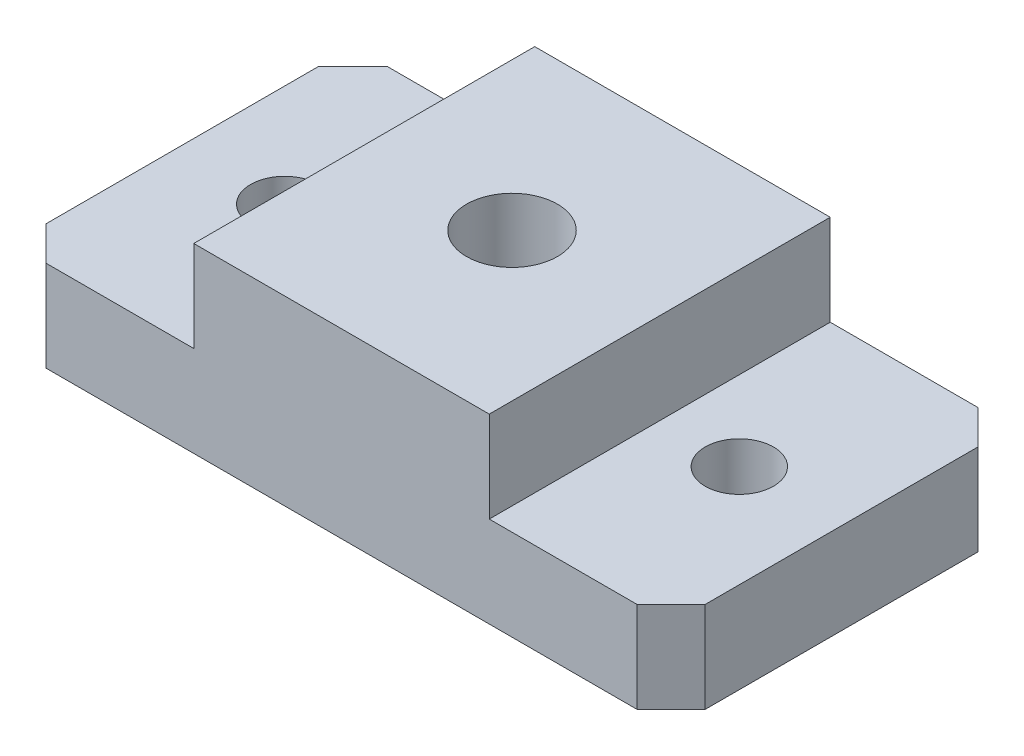
SolidWorks part; units mm, degrees
ref_plane "Front Plane" through (0, 0, 0) normal (0, 0, 1) x (1, 0, 0)
ref_plane "Top Plane" through (0, 0, 0) normal (0, 1, 0) x (1, 0, 0)
ref_plane "Right Plane" through (0, 0, 0) normal (1, 0, 0) x (0, 0, -1)
sketch "Sketch1" plane through (0, 0, 0) normal (0, 1, 0) x (1, 0, 0)
  line L0 (-20, 0) -> (20, 0) construction
  line L1 (-29, 15) -> (29, 15)
  line L2 (-29, 15) -> (-29, -15)
  line L3 (-29, -15) -> (29, -15)
  line L4 (29, 15) -> (29, -15)
  line L5 (-29, 15) -> (29, -15) construction
  line L6 (-29, -15) -> (29, 15) construction
  circle A0 centre (-20, 0) radius 3
  circle A1 centre (20, 0) radius 3
  point P0 (0, 0)
  point P13 (0, 0)
  dimension "D3" = 6
  dimension "D1" = 30
  dimension "D2" = 58
  dimension "D4" = 40
extrude "Boss-Extrude1" add sketch "Sketch1" along normal blind 8
sketch "Sketch2" plane through (0, 8, 0) normal (0, 1, 0) x (1, 0, 0)
  line L1 (-13, 15) -> (13, 15)
  line L2 (-13, 15) -> (-13, -15)
  line L3 (-13, -15) -> (13, -15)
  line L4 (13, 15) -> (13, -15)
  line L5 (-13, 15) -> (13, -15) construction
  line L6 (-13, -15) -> (13, 15) construction
  point P0 (0, 0)
  dimension "D1" = 30
  dimension "D2" = 26
extrude "Boss-Extrude2" add sketch "Sketch2" along normal blind 8
sketch "Sketch3" plane through (0, 16, 0) normal (0, 1, 0) x (1, 0, 0)
  circle A0 centre (0, 0) radius 4
  dimension "D1" = 8
extrude "Cut-Extrude1" cut sketch "Sketch3" against normal through all
chamfer "Chamfer1" distance 3 angle 45 4 edges at (29, 4, 15) (29, 4, -15) (-29, 4, -15) (-29, 4, 15)
sketch "Sketch4" plane through (0, 8, 0) normal (0, 1, 0) x (1, 0, 0)
  circle A0 centre (-20, 0) radius 4.25
  dimension "D1" = 8.5
